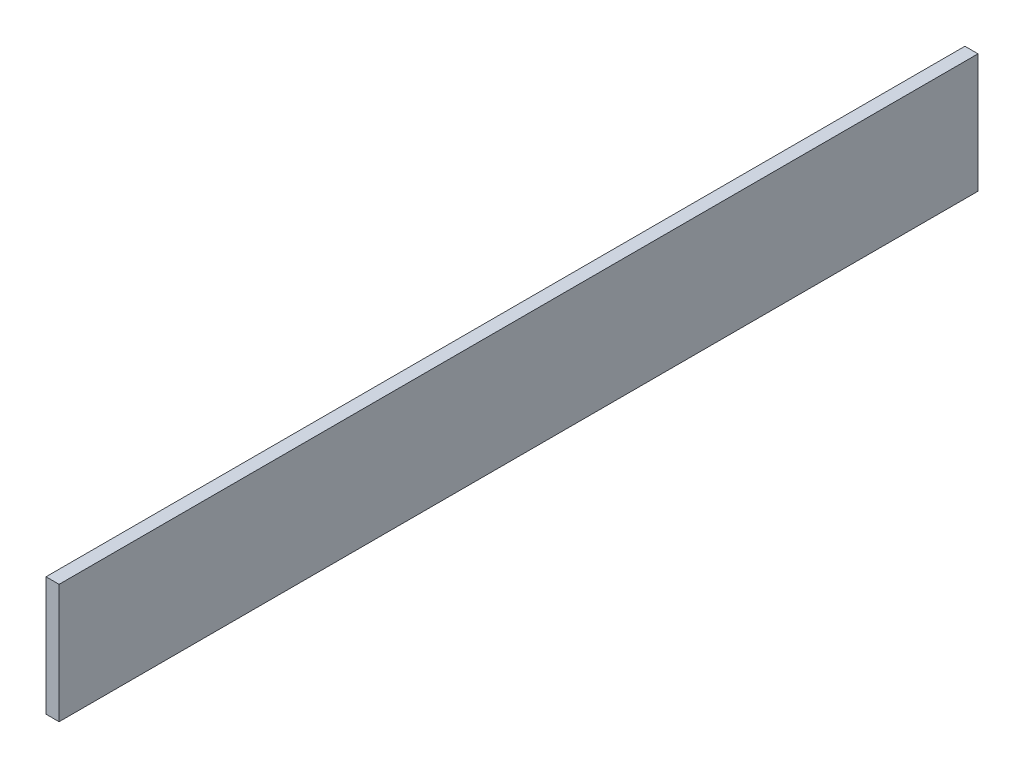
SolidWorks part; units mm, degrees
ref_plane "Front Plane" through (0, 0, 0) normal (0, 0, 1) x (1, 0, 0)
ref_plane "Top Plane" through (0, 0, 0) normal (0, 1, 0) x (1, 0, 0)
ref_plane "Right Plane" through (0, 0, 0) normal (1, 0, 0) x (0, 0, -1)
ref_plane "Plane1"
sketch "Sketch1" plane through (0, 0, 0) normal (1, 0, 0) x (0, 1, 0)
  line L0 (-100, 772) -> (100, 772)
  line L1 (100, 772) -> (100, -772)
  line L2 (100, -772) -> (-100, -772)
  line L3 (-100, -772) -> (-100, 772)
extrude "Extrusion1" add sketch "Sketch1" along normal blind 22
